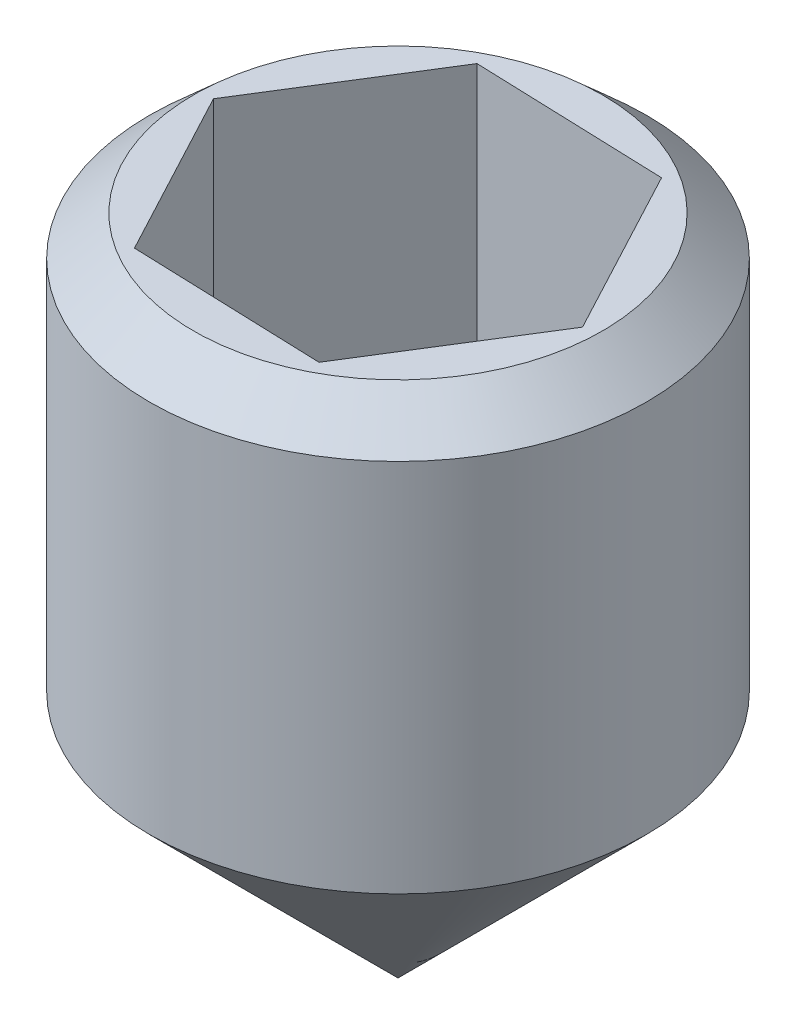
SolidWorks part; units mm, degrees
ref_plane "Спереди" through (0, 0, 0) normal (0, 0, 1) x (1, 0, 0)
ref_plane "Сверху" through (0, 0, 0) normal (0, 1, 0) x (1, 0, 0)
ref_plane "Справа" through (0, 0, 0) normal (1, 0, 0) x (0, 0, -1)
sketch "Эскиз1" plane through (0, 0, 0) normal (0, 0, 1) x (1, 0, 0)
  line L0 (0, 0) -> (0, 4)
  line L1 (0, 4) -> (-1.2344, 4)
  line L2 (-1.2344, 4) -> (-1.5, 3.7611)
  line L3 (-1.5, 3.7611) -> (-1.5, 1.5)
  line L4 (-1.5, 1.5) -> (0, 0)
  dimension "D1" = 45
  dimension "D2" = 4
  dimension "D3" = 1.5
revolve "Повернуть1" add sketch "Эскиз1" angle 360 about L0
sketch "Эскиз2" plane through (0, 4, 0) normal (0, 1, 0) x (1, 0, 0)
  line L1 (-0.6116, -0.9794) -> (0.5424, -1.0194)
  line L2 (0.5424, -1.0194) -> (1.154, -0.04)
  line L3 (1.154, -0.04) -> (0.6116, 0.9794)
  line L4 (0.6116, 0.9794) -> (-0.5424, 1.0194)
  line L5 (-0.5424, 1.0194) -> (-1.154, 0.04)
  line L6 (-1.154, 0.04) -> (-0.6116, -0.9794)
  circle A0 centre (0, 0) radius 1 construction
  dimension "D1" = 2
extrude "Вырез-Вытянуть1" cut sketch "Эскиз2" against normal blind 2
